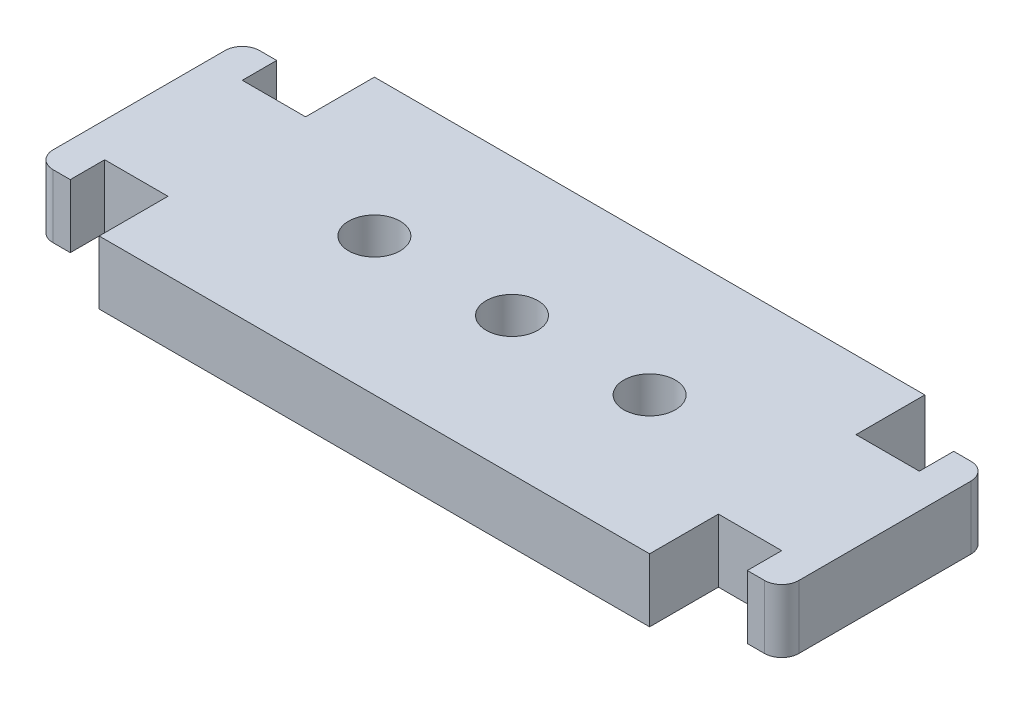
SolidWorks part; units mm, degrees
ref_plane "Front Plane" through (0, 0, 0) normal (0, 0, 1) x (1, 0, 0)
ref_plane "Top Plane" through (0, 0, 0) normal (0, 1, 0) x (1, 0, 0)
ref_plane "Right Plane" through (0, 0, 0) normal (1, 0, 0) x (0, 0, -1)
sketch "Sketch1" plane through (0, 0, 0) normal (0, 1, 0) x (1, 0, 0)
  line L0 (-25.4, 0) -> (25.4, 0) construction
  line L1 (-25.4, -12.7) -> (25.4, -12.7)
  line L2 (-25.4, -12.7) -> (-25.4, -6.35)
  line L3 (-25.4, 12.7) -> (25.4, 12.7)
  line L4 (25.4, -12.7) -> (25.4, -6.35)
  line L5 (-25.4, -12.7) -> (25.4, 12.7) construction
  line L6 (-25.4, 12.7) -> (25.4, -12.7) construction
  line L7 (31.242, -6.35) -> (25.4, -6.35)
  line L9 (31.242, 6.35) -> (25.4, 6.35)
  line L10 (0, -12.7) -> (0, 12.7) construction
  line L11 (31.242, -6.35) -> (25.4, 6.35) construction
  line L12 (31.242, 6.35) -> (25.4, -6.35) construction
  line L13 (25.4, 6.35) -> (25.4, 12.7)
  line L14 (-31.242, 6.35) -> (-25.4, -6.35) construction
  line L15 (-31.242, -6.35) -> (-25.4, 6.35) construction
  line L16 (-31.242, 6.35) -> (-25.4, 6.35)
  line L17 (-31.242, 6.35) -> (-31.242, 9.525)
  line L18 (-31.242, -6.35) -> (-25.4, -6.35)
  line L19 (-25.4, 6.35) -> (-25.4, 12.7)
  line L20 (34.417, 9.525) -> (31.242, -9.525) construction
  line L21 (-34.417, -9.525) -> (-31.242, -9.525)
  line L22 (-34.417, -9.525) -> (-34.417, 9.525)
  line L23 (-34.417, 9.525) -> (-31.242, 9.525)
  line L24 (-31.242, -9.525) -> (-31.242, -6.35)
  line L25 (-34.417, -9.525) -> (-31.242, 9.525) construction
  line L26 (-34.417, 9.525) -> (-31.242, -9.525) construction
  line L27 (34.417, -9.525) -> (31.242, 9.525) construction
  line L28 (31.242, -9.525) -> (31.242, -6.35)
  line L29 (34.417, 9.525) -> (31.242, 9.525)
  line L30 (34.417, -9.525) -> (34.417, 9.525)
  line L31 (34.417, -9.525) -> (31.242, -9.525)
  line L32 (31.242, 6.35) -> (31.242, 9.525)
  point P0 (0, 0)
  point P6 (28.321, 0)
  point P19 (-28.321, 0)
  point P20 (-32.8295, 0)
  point P29 (32.8295, 0)
  dimension "D1" = 25.4
  dimension "D2" = 50.8
  dimension "D3" = 12.7
  dimension "D4" = 5.842
  dimension "D5" = 3.175
  dimension "D6" = 19.05
extrude "Boss-Extrude1" add sketch "Sketch1" along normal blind 5.842
fillet "Fillet1" radius 1.5875 4 edges at (34.417, 2.921, 9.525) (34.417, 2.921, -9.525) (-34.417, 2.921, 9.525) (-34.417, 2.921, -9.525)
sketch "Sketch2" plane through (0, 5.842, 0) normal (0, 1, 0) x (1, 0, 0)
  line L0 (-34.417, 0) -> (34.417, 0) construction
  line L1 (-34.417, 7.9375) -> (-34.417, -7.9375) construction
  line L2 (34.417, -7.9375) -> (34.417, 7.9375) construction
  line L3 (0, 12.7) -> (0, -12.7) construction
  line L4 (25.4, 12.7) -> (-25.4, 12.7) construction
  line L5 (-25.4, -12.7) -> (25.4, -12.7) construction
  circle A0 centre (0, 0) radius 2.3813
  circle A1 centre (12.7, 0) radius 2.3813
  circle A2 centre (-12.7, 0) radius 2.3813
  dimension "D1" = 4.7625
  dimension "D2" = 2
extrude "Cut-Extrude1" cut sketch "Sketch2" against normal through all
